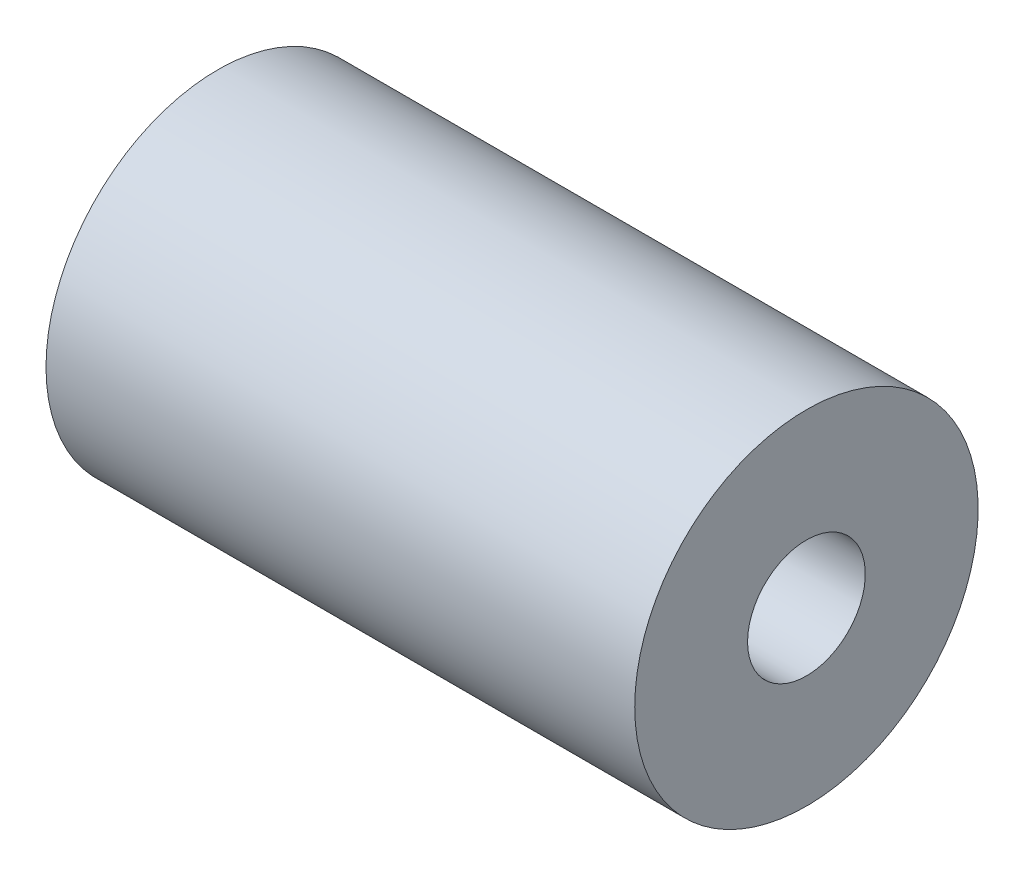
SolidWorks part; units mm, degrees
material "Alumina"
ref_plane "Front Plane" through (0, 0, 0) normal (0, 0, 1) x (1, 0, 0)
ref_plane "Top Plane" through (0, 0, 0) normal (0, 1, 0) x (1, 0, 0)
ref_plane "Right Plane" through (0, 0, 0) normal (1, 0, 0) x (0, 0, -1)
sketch "Axial profile (mm)" plane through (0, 0, 0) normal (0, 0, 1) x (1, 0, 0)
  line L0 (-110, 0) -> (75, 0) construction
  line L1 (73, 2.4) -> (97, 2.4)
  line L2 (97, 2.4) -> (97, 7)
  line L3 (97, 7) -> (73, 7)
  line L4 (73, 7) -> (73, 2.4)
revolve "Full revolution" add sketch "Axial profile (mm)" angle 360 about L0
